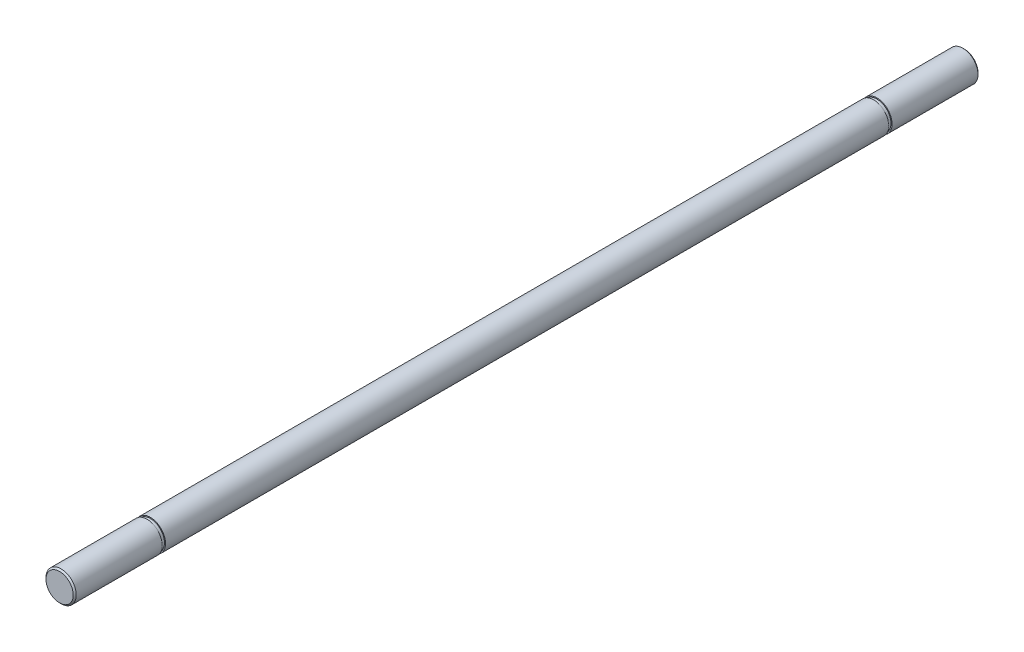
SolidWorks part; units mm, degrees
ref_plane "前视基准面" through (0, 0, 0) normal (0, 0, 1) x (1, 0, 0)
ref_plane "上视基准面" through (0, 0, 0) normal (0, 1, 0) x (1, 0, 0)
ref_plane "右视基准面" through (0, 0, 0) normal (1, 0, 0) x (0, 0, -1)
sketch "草图1" plane through (0, 0, 0) normal (0, 0, 1) x (1, 0, 0)
  circle A0 centre (0, 0) radius 5
  dimension "D1" = 10
extrude "拉伸1" add sketch "草图1" along normal mid plane 299
sketch "草图2" plane through (0, 0, 0) normal (0, 1, 0) x (1, 0, 0)
  line L0 (5, -149.5) -> (5, 149.5) construction
  line L1 (4.65, 120.6) -> (10.6716, 120.6)
  line L2 (4.65, 120.6) -> (4.65, 119.5)
  line L3 (4.65, 119.5) -> (10.6716, 119.5)
  line L4 (10.6716, 120.6) -> (10.6716, 119.5)
  line L5 (4.65, -119.5) -> (10.6716, -119.5)
  line L6 (4.65, -119.5) -> (4.65, -120.6)
  line L7 (4.65, -120.6) -> (10.6716, -120.6)
  line L8 (10.6716, -119.5) -> (10.6716, -120.6)
  dimension "D1" = 119.5
  dimension "D2" = 119.5
  dimension "D3" = 0.35
  dimension "D4" = 1.1
  dimension "D5" = 0.35
  dimension "D6" = 1.1
revolve "切除-旋转1" cut sketch "草图2" angle 360 about axis through (0, 0, 149.5) along (0, 0, -1)
chamfer "倒角1" distance 0.5 angle 45 2 edges at (5, 0, 149.5) (5, 0, -149.5)
